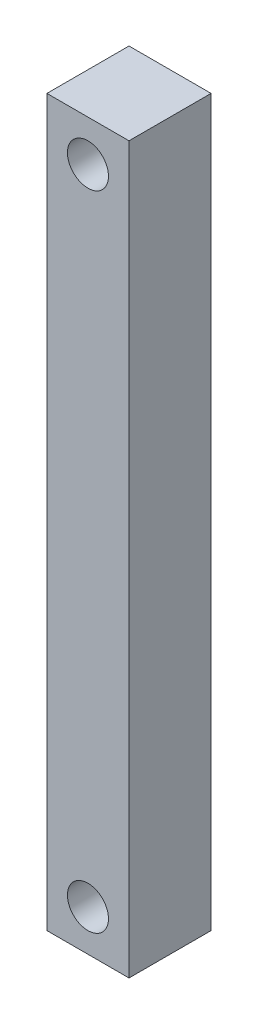
SolidWorks part; units mm, degrees
ref_plane "前视基准面" through (0, 0, 0) normal (0, 0, 1) x (1, 0, 0)
ref_plane "上视基准面" through (0, 0, 0) normal (0, 1, 0) x (1, 0, 0)
ref_plane "右视基准面" through (0, 0, 0) normal (1, 0, 0) x (0, 0, -1)
other "Configuration Table"
sketch "草图1" plane through (0, 0, 0) normal (0, 0, 1) x (1, 0, 0)
  line L1 (3, -26.5) -> (-3, -26.5)
  line L2 (3, -26.5) -> (3, 26.5)
  line L3 (3, 26.5) -> (-3, 26.5)
  line L4 (-3, -26.5) -> (-3, 26.5)
  line L5 (3, -26.5) -> (-3, 26.5) construction
  line L6 (3, 26.5) -> (-3, -26.5) construction
  point P0 (0, 0)
  dimension "D1" = 53
  dimension "D2" = 6
extrude "凸台-拉伸1" add sketch "草图1" along normal blind 6
sketch "草图2" plane through (0, 0, 6) normal (0, 0, 1) x (1, 0, 0)
  line L0 (0, 0) -> (0, 23.5) construction
  line L1 (0, 0) -> (3, 0) construction
  line L2 (3, -26.5) -> (3, 26.5) construction
  circle A0 centre (0, 23.5) radius 1.5
  circle A1 centre (0, -23.5) radius 1.5
  dimension "D2" = 3
  dimension "D1" = 23.5
extrude "切除-拉伸1" cut sketch "草图2" against normal blind 6
